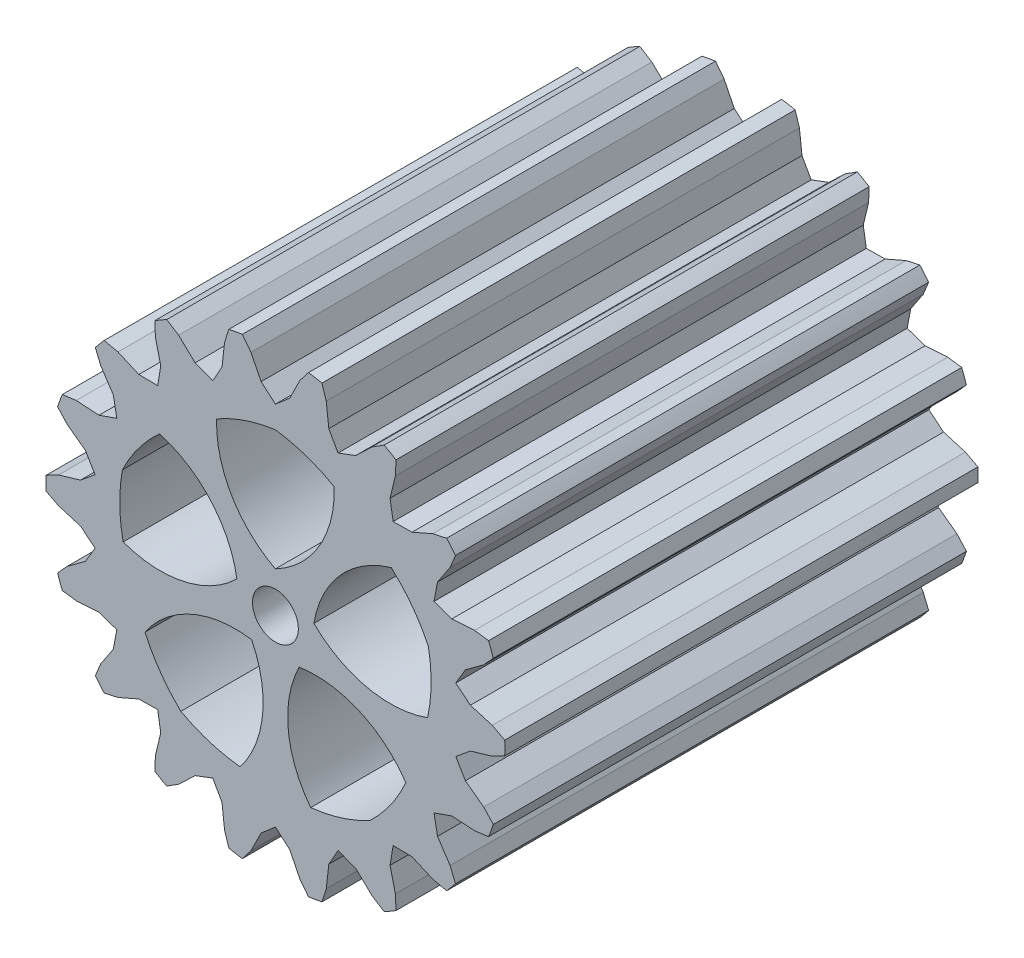
SolidWorks part; units mm, degrees
ref_plane "Front Plane" through (0, 0, 0) normal (0, 0, 1) x (1, 0, 0)
ref_plane "Top Plane" through (0, 0, 0) normal (0, 1, 0) x (1, 0, 0)
ref_plane "Right Plane" through (0, 0, 0) normal (1, 0, 0) x (0, 0, -1)
sketch "Sketch1" plane through (0, 0, 0) normal (0, 0, 1) x (1, 0, 0)
  line L1 (1.2374, -1.2374) -> (-1.2374, -1.2374) construction
  line L2 (1.2374, -1.2374) -> (1.2374, 1.2374) construction
  line L3 (1.2374, 1.2374) -> (-1.2374, 1.2374) construction
  line L4 (-1.2374, -1.2374) -> (-1.2374, 1.2374) construction
  line L5 (1.2374, -1.2374) -> (-1.2374, 1.2374) construction
  line L6 (1.2374, 1.2374) -> (-1.2374, -1.2374) construction
  circle A0 centre (0, 0) radius 16
  circle A1 centre (0, 0) radius 1.75 construction
  dimension "D1" = 32
  dimension "D2" = 3.5
extrude "Boss-Extrude1" add sketch "Sketch1" along normal blind 33
sketch "Sketch2" plane through (0, 0, 0) normal (0, 0, 1) x (1, 0, 0)
  line L0 (0, 0) -> (0, 10.088) construction
  line L1 (0, 12.7713) -> (-0.9985, 13.6307)
  line L8 (-1.7043, 16.6161) -> (0, 17.3303)
  line L11 (-0.9985, 13.6307) -> (-1.7043, 15.0517)
  line L12 (-1.7043, 15.0517) -> (-2.3066, 15.8329)
  line L13 (-2.3066, 15.8329) -> (-1.7043, 16.6161)
  line L14 (2.3066, 15.8329) -> (1.7043, 16.6161)
  line L15 (1.7043, 15.0517) -> (2.3066, 15.8329)
  line L16 (0.9985, 13.6307) -> (1.7043, 15.0517)
  line L17 (1.7043, 16.6161) -> (0, 17.3303)
  line L18 (0, 12.7713) -> (0.9985, 13.6307)
  circle A14 centre (0, 0) radius 16 construction
  point P4 (0, 10.4739)
  point P16 (0, 16)
  point P17 (0, 0)
  point P18 (0, 15.0509)
  point P19 (-1.8718, 13.622)
  point P20 (-2.3066, 13.5594)
  point P21 (-1.9403, 13.7912)
  point P22 (-2.3066, 13.3759)
  point P23 (-2.2968, 15.8343)
  point P24 (-1.7043, 16.6161)
  point P25 (0, 17.3303)
  dimension "D5" = 0.6023
  dimension "D6" = 0.7811
  dimension "D1" = 0.9985
  dimension "D2" = 0.8594
  dimension "D3" = 0.7058
  dimension "D4" = 1.4211
extrude "Cut-Extrude1" cut sketch "Sketch2" along normal through all
sketch "Sketch3" plane through (0, 0, 0) normal (0, 0, 1) x (1, 0, 0)
  circle A0 centre (0, 0) radius 7.5
  dimension "D1" = 15
sketch "Sketch4" plane through (0, 0, 33) normal (0, 0, 1) x (1, 0, 0)
  circle A0 centre (0, 0) radius 1.6
  dimension "D1" = 3.2
extrude "Cut-Extrude2" cut sketch "Sketch4" against normal through all both and the other way through all
pattern_circular "CirPattern1" count 18 over 360 about axis through (0, 0, 0) along (0, 0, 1) of "Cut-Extrude1"
sketch "Sketch5" plane through (0, 0, 0) normal (0, 0, 1) x (1, 0, 0)
  line L0 (0, 0) -> (0, 16.5734) construction
  arc A0 (0, 2.8219) -> (-4.1006, 9.8315) centre (3.5128, 9.581) cw
  arc A1 (-4.1006, 9.8315) -> (0, 11.2208) centre (1.4476, 0.2015) cw
  arc A2 (4.1006, 9.8315) -> (0, 11.2208) centre (-1.4476, 0.2015) ccw
  arc A3 (0, 2.8219) -> (4.1006, 9.8315) centre (-3.5128, 9.581) ccw
  point P7 (2.1966, 7.8938)
  point P12 (0, 2.8219)
  point P13 (-3.7456, 8.3732)
  point P14 (0, 11.1959)
  point P15 (-4.1006, 9.8315)
  point P16 (0, 11.2208)
extrude "Cut-Extrude4" cut sketch "Sketch5" along normal through all both and the other way through all
pattern_circular "CirPattern2" count 5 over 360 about axis through (0, 0, 0) along (0, 0, 1) of "Cut-Extrude4"
equation "\"circle\"=32"
equation "\"D1@Sketch1\"=\"circle\""
equation "\"separator_width\"=45"
equation "\"big-gear-thiccness\"=2"
equation "\"D1@Boss-Extrude1\"=\"separator_width\" - \"big-gear-thiccness\"-10"
